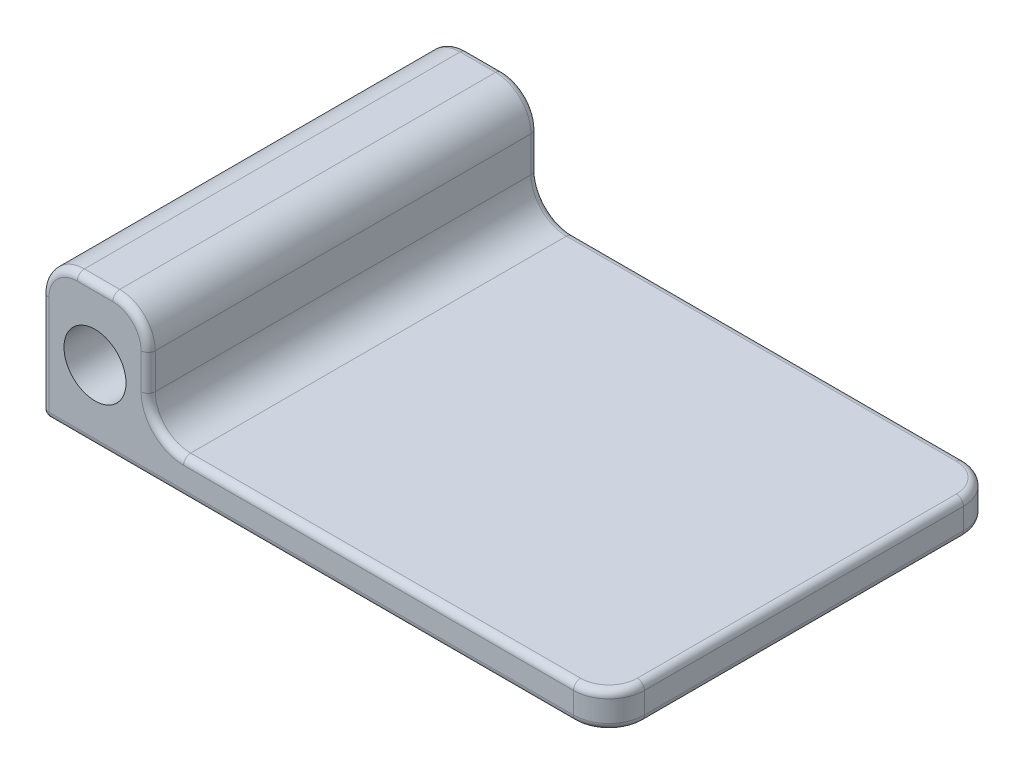
SolidWorks part; units mm, degrees
ref_plane "Front Plane" through (0, 0, 0) normal (0, 0, 1) x (1, 0, 0)
ref_plane "Top Plane" through (0, 0, 0) normal (0, 1, 0) x (1, 0, 0)
ref_plane "Right Plane" through (0, 0, 0) normal (1, 0, 0) x (0, 0, -1)
sketch "Sketch1" plane through (0, 0, 0) normal (0, 1, 0) x (1, 0, 0)
  line L1 (-101.6, 69.85) -> (101.6, 69.85)
  line L2 (-101.6, 69.85) -> (-101.6, -69.85)
  line L3 (-101.6, -69.85) -> (101.6, -69.85)
  line L4 (101.6, 69.85) -> (101.6, -69.85)
  line L5 (-101.6, 69.85) -> (101.6, -69.85) construction
  line L6 (-101.6, -69.85) -> (101.6, 69.85) construction
  point P0 (0, 0)
  dimension "D1" = 203.2
  dimension "D2" = 139.7
extrude "Boss-Extrude1" add sketch "Sketch1" along normal blind 50.8
sketch "Sketch2" plane through (0, 0, 69.85) normal (0, 0, 1) x (1, 0, 0)
  line L0 (-101.6, 50.8) -> (-101.6, 0) construction
  line L1 (101.6, 50.8) -> (-63.5, 50.8)
  line L2 (101.6, 50.8) -> (101.6, 12.7)
  line L3 (101.6, 12.7) -> (-63.5, 12.7)
  line L4 (-63.5, 50.8) -> (-63.5, 12.7)
  line L5 (-101.6, 0) -> (101.6, 0) construction
  dimension "D1" = 38.1
  dimension "D2" = 12.7
extrude "Cut-Extrude1" cut sketch "Sketch2" against normal through all
sketch "Sketch3" plane through (0, 0, 69.85) normal (0, 0, 1) x (1, 0, 0)
  line L0 (-82.55, 50.8) -> (-82.55, 0) construction
  line L1 (-101.6, 50.8) -> (-63.5, 50.8) construction
  line L2 (-101.6, 0) -> (101.6, 0) construction
  circle A0 centre (-82.55, 25.4) radius 11.1125
  dimension "D1" = 22.225
extrude "Cut-Extrude2" cut sketch "Sketch3" against normal through all
fillet "Fillet1" radius 12.7 3 edges at (-63.5, 12.7, 0) (-101.6, 50.8, 0) (-63.5, 50.8, 0)
fillet "Fillet3" radius 12.7 2 edges at (101.6, 6.35, -69.85) (101.6, 6.35, 69.85)
fillet "Fillet2" radius 2.54 23 edges at (19.05, 12.7, -69.85) (-59.7803, 16.4197, -69.85) (-63.5, 31.75, -69.85) (-67.2197, 47.0803, -69.85) (-82.55, 50.8, -69.85) (-97.8803, 47.0803, -69.85) (19.05, 12.7, 69.85) (-59.7803, 16.4197, 69.85) (-63.5, 31.75, 69.85) (-67.2197, 47.0803, 69.85) (-82.55, 50.8, 69.85) (-97.8803, 47.0803, 69.85) (101.6, 0, 0) (101.6, 12.7, 0) (-6.35, 0, -69.85) (-6.35, 0, 69.85) (-101.6, 19.05, -69.85) (-101.6, 19.05, 69.85) (-101.6, 0, 0) (97.8803, 0, -66.1303) (97.8803, 0, 66.1303) (97.8803, 12.7, -66.1303) (97.8803, 12.7, 66.1303)
